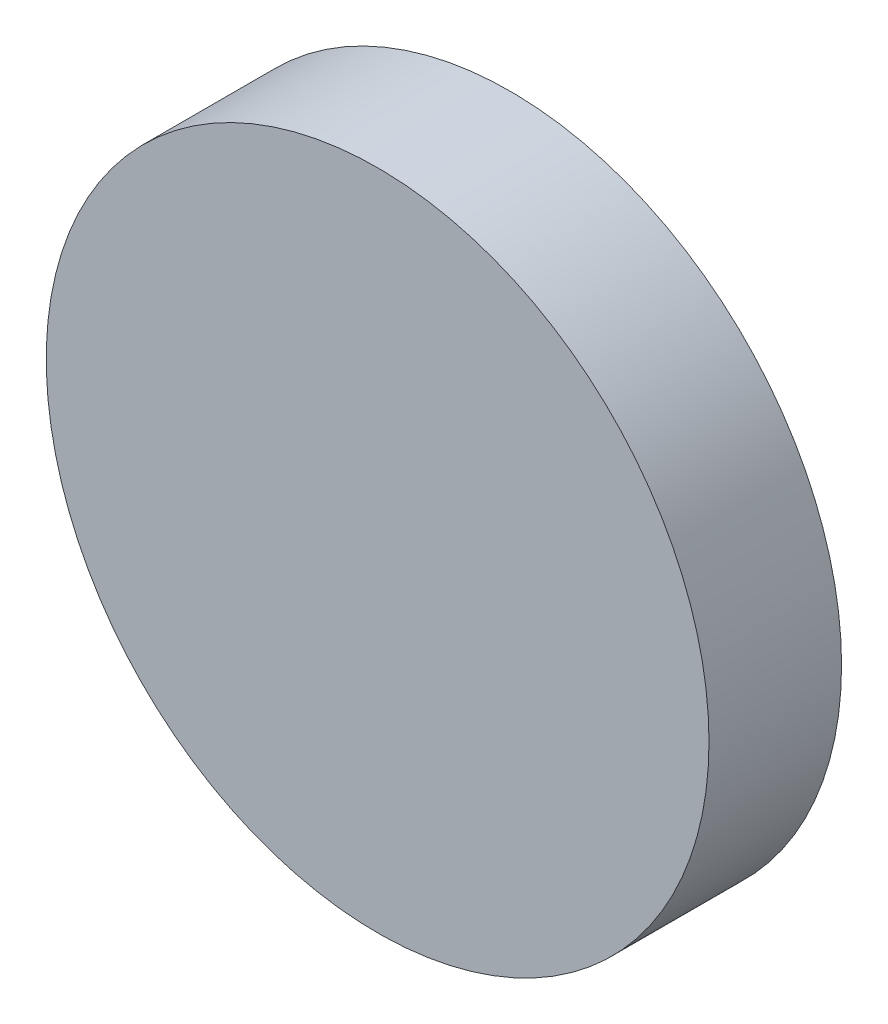
SolidWorks part; units mm, degrees
ref_plane "前基準面" through (0, 0, 0) normal (0, 0, 1) x (1, 0, 0)
ref_plane "上基準面" through (0, 0, 0) normal (0, 1, 0) x (1, 0, 0)
ref_plane "右基準面" through (0, 0, 0) normal (1, 0, 0) x (0, 0, -1)
sketch "草圖1" plane through (0, 0, 0) normal (0, 0, 1) x (1, 0, 0)
  circle A0 centre (0, 0) radius 12.5
  dimension "D1" = 25
extrude "填料-伸長1" add sketch "草圖1" along normal blind 5
